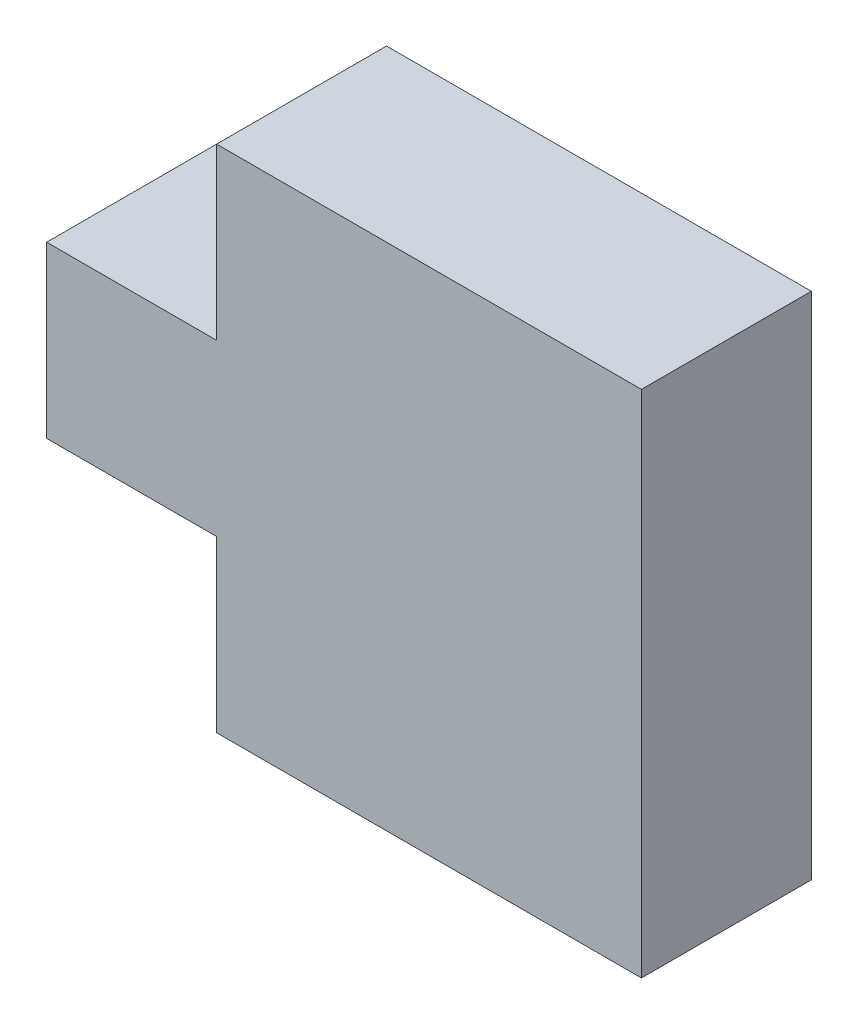
SolidWorks part; units mm, degrees
ref_plane "Front Plane" through (0, 0, 0) normal (0, 0, 1) x (1, 0, 0)
ref_plane "Top Plane" through (0, 0, 0) normal (0, 1, 0) x (1, 0, 0)
ref_plane "Right Plane" through (0, 0, 0) normal (1, 0, 0) x (0, 0, -1)
sketch "Sketch1" plane through (0, 0, 0) normal (0, 0, 1) x (1, 0, 0)
  line L0 (0, 40) -> (-20, 40)
  line L1 (0, 0) -> (50, 0)
  line L2 (0, 0) -> (0, 20)
  line L3 (0, 60) -> (50, 60)
  line L4 (50, 0) -> (50, 60)
  line L5 (-20, 40) -> (-20, 20)
  line L6 (-20, 20) -> (0, 20)
  line L7 (0, 40) -> (0, 60)
  dimension "D1" = 50
  dimension "D2" = 60
  dimension "D3" = 20
  dimension "D4" = 20
  dimension "D5" = 20
extrude "Boss-Extrude1" add sketch "Sketch1" along normal blind 20
